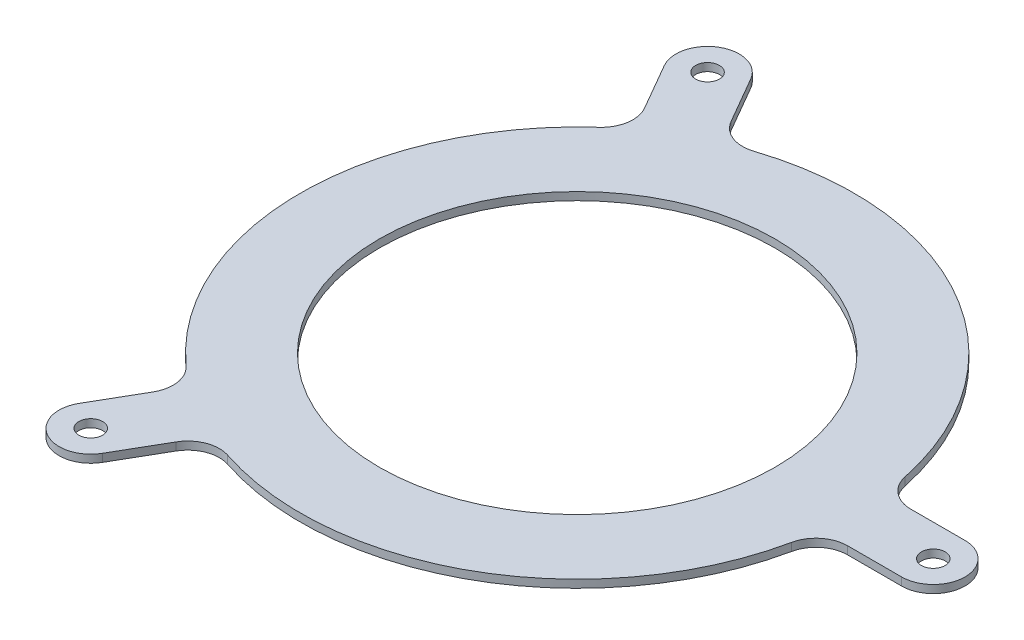
SolidWorks part; units mm, degrees
ref_plane "Front Plane" through (0, 0, 0) normal (0, 0, 1) x (1, 0, 0)
ref_plane "Top Plane" through (0, 0, 0) normal (0, 1, 0) x (1, 0, 0)
ref_plane "Right Plane" through (0, 0, 0) normal (1, 0, 0) x (0, 0, -1)
sketch "Sketch1" plane through (0, 0, 0) normal (0, 1, 0) x (1, 0, 0)
  line L0 (-55.3074, 0) -> (69.7133, 0) construction
  line L1 (-29.6642, 51.3799) -> (32.3799, -56.0836) construction
  line L3 (45, 4) -> (34.7707, 4)
  line L4 (45, -4) -> (34.7707, -4)
  line L5 (-19.0359, -40.9711) -> (-13.9212, -32.1123)
  line L6 (-25.9641, -36.9711) -> (-20.8494, -28.1123)
  line L7 (27.6537, 47.8976) -> (-34.8567, -60.3735) construction
  line L8 (-25.9641, 36.9711) -> (-20.8494, 28.1123)
  line L9 (-19.0359, 40.9711) -> (-13.9212, 32.1123)
  line L11 (27.6537, -47.8976) -> (-34.8567, 60.3735) construction
  circle A0 centre (0, 0) radius 45 construction
  circle A1 centre (0, 0) radius 25
  circle A2 centre (0, 0) radius 35
  circle A3 centre (45, 0) radius 1.5
  circle A5 centre (-22.5, -38.9711) radius 1.5
  circle A8 centre (45, 0) radius 4 construction
  arc A9 (45, 4) -> (44.9994, -4) centre (45, 0) cw
  circle A10 centre (-22.5, -38.9711) radius 1.5
  arc A11 (-19.0359, -40.9711) -> (-25.9638, -36.9706) centre (-22.5, -38.9711) cw
  circle A12 centre (-22.5, -38.9711) radius 4 construction
  circle A13 centre (-22.5, 38.9711) radius 1.5
  arc A14 (-25.9641, 36.9711) -> (-19.0356, 40.9706) centre (-22.5, 38.9711) cw
  circle A15 centre (-22.5, 38.9711) radius 4 construction
  point P9 (0, 0)
  point P43 (0, 0)
  dimension "D1" = 90
  dimension "D2" = 50
  dimension "D3" = 70
  dimension "D6" = 3
  dimension "D7" = 8
  dimension "D4" = 3
extrude "Boss-Extrude1" add sketch "Sketch1" along normal blind 1 contours A2 A1 | A14 L8 A2 L9 A13 | A11 L5 A2 L6 A5 | A9 L3 A2 L4 A3
fillet "Fillet1" radius 4 6 edges at (-13.9212, 0.5, 32.1123) (-20.8494, 0.5, 28.1123) (-20.8494, 0.5, -28.1123) (-13.9212, 0.5, -32.1123) (34.7707, 0.5, -4) (34.7707, 0.5, 4)
